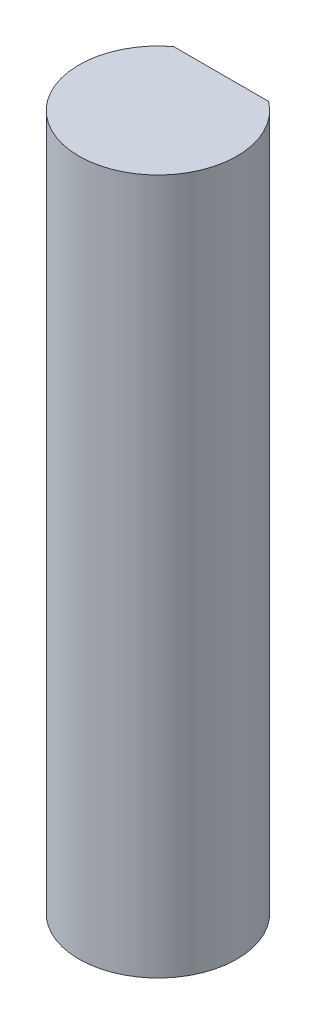
SolidWorks part; units mm, degrees
ref_plane "Front Plane" through (0, 0, 0) normal (0, 0, 1) x (1, 0, 0)
ref_plane "Top Plane" through (0, 0, 0) normal (0, 1, 0) x (1, 0, 0)
ref_plane "Right Plane" through (0, 0, 0) normal (1, 0, 0) x (0, 0, -1)
sketch "Sketch1" plane through (0, 0, 0) normal (0, 1, 0) x (1, 0, 0)
  circle A0 centre (0, 0) radius 2.5
  dimension "D1" = 5
extrude "Boss-Extrude1" add sketch "Sketch1" along normal blind 22
sketch "Sketch2" plane through (0, 22, 0) normal (0, 1, 0) x (1, 0, 0)
  line L0 (0, 2.5) -> (0, 0) construction
  line L1 (-2.75, 2) -> (2.75, 2)
  line L2 (-2.75, 2) -> (-2.75, 3)
  line L3 (-2.75, 3) -> (2.75, 3)
  line L4 (2.75, 2) -> (2.75, 3)
  line L5 (-2.75, 2) -> (2.75, 3) construction
  line L6 (-2.75, 3) -> (2.75, 2) construction
  circle A0 centre (0, 0) radius 2.5
  circle A1 centre (0, 0) radius 2.5 construction
  point P0 (0, 2.5)
  point P8 (0, 0)
  circle M2 centre (0, 0) radius 2.5
  dimension "D1" = 0.5
  dimension "D2" = 5.5
extrude "Cut-Extrude1" cut sketch "Sketch2" against normal blind 15 contours L1 M2
